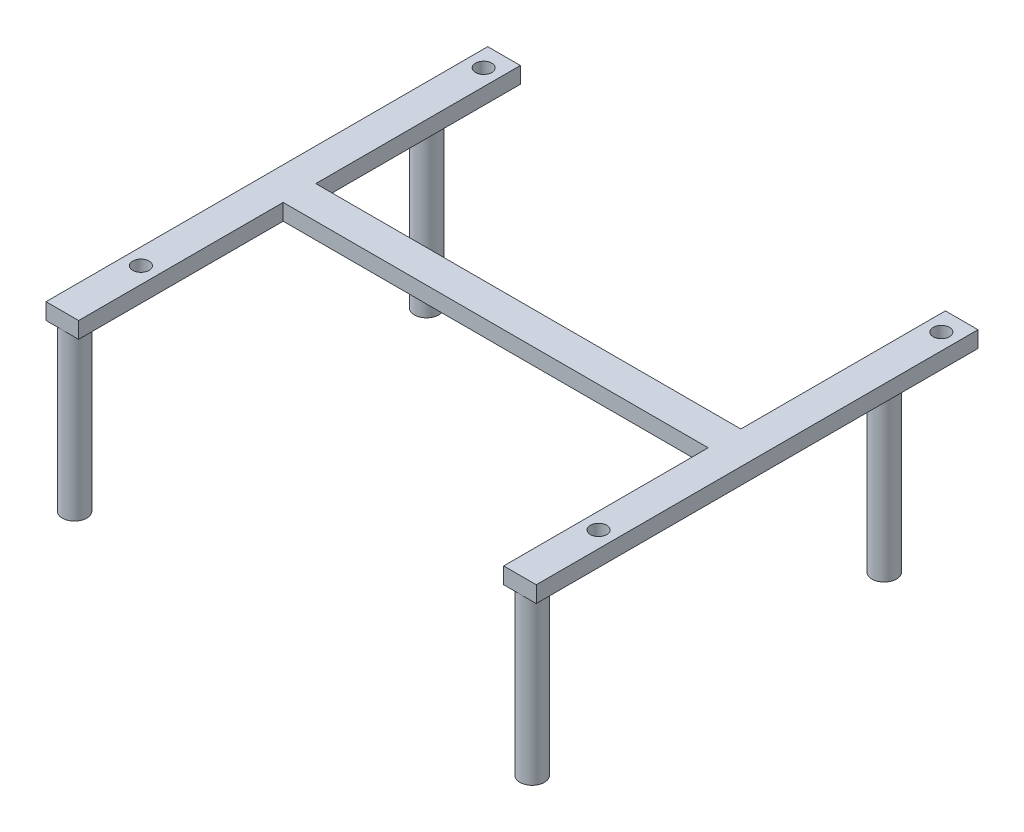
SolidWorks part; units mm, degrees
ref_plane "前视基准面" through (0, 0, 0) normal (0, 0, 1) x (1, 0, 0)
ref_plane "上视基准面" through (0, 0, 0) normal (0, 1, 0) x (1, 0, 0)
ref_plane "右视基准面" through (0, 0, 0) normal (1, 0, 0) x (0, 0, -1)
other "Configuration Table"
sketch "草图1" plane through (0, 0, 0) normal (0, 1, 0) x (1, 0, 0)
  line L0 (0, 43.18) -> (0, 0) construction
  line L1 (56.13, 43.18) -> (0, 43.18) construction
  line L2 (56.13, 0) -> (56.13, 43.18) construction
  line L3 (28.065, 43.18) -> (28.065, 39.1656) construction
  line L4 (56.13, 43.18) -> (0, 43.18) construction
  circle A0 centre (0, 0) radius 1.5
  circle A1 centre (0, 43.18) radius 1.5
  circle A2 centre (56.13, 43.18) radius 1.5
  circle A3 centre (56.13, 0) radius 1.5
  point P10 (28.065, 43.18)
  dimension "D1" = 3
  dimension "D2" = 3
  dimension "D4" = 3
  dimension "D6" = 3
  dimension "D3" = 43.18
  dimension "D5" = 56.13
  dimension "D7" = 43.18
extrude "凸台-拉伸1" add sketch "草图1" along normal blind 20
sketch "草图2" plane through (0, 20, 0) normal (0, 1, 0) x (1, 0, 0)
  line L0 (-2, 52.68) -> (-2, -1.5)
  line L1 (-2, -1.5) -> (2, -1.5)
  line L3 (2, 52.68) -> (-2, 52.68)
  line L5 (54.13, -1.5) -> (58.13, -1.5)
  line L6 (58.13, -1.5) -> (58.13, 52.68)
  line L7 (58.13, 52.68) -> (54.13, 52.68)
  line L8 (2, 27.59) -> (54.13, 27.59)
  line L10 (54.13, 23.59) -> (2, 23.59)
  line L13 (54.13, 52.68) -> (54.13, 27.59)
  line L14 (2, 52.68) -> (2, 27.59)
  line L15 (2, 23.59) -> (2, -1.5)
  line L16 (54.13, 23.59) -> (54.13, -1.5)
  circle A0 centre (0, 43.18) radius 1.5 construction
  circle A1 centre (0, 0) radius 1.5 construction
  circle A2 centre (56.13, 43.18) radius 1.5 construction
  circle A4 centre (56.13, 0) radius 1.5 construction
  point P22 (-2, 25.59)
  dimension "D8" = 2
  dimension "D1" = 9.5
  dimension "D2" = 9.5
  dimension "D3" = 4
  dimension "D4" = 2
  dimension "D5" = 4
  dimension "D6" = 2
  dimension "D7" = 4
extrude "凸台-拉伸2" add sketch "草图2" along normal blind 2
sketch "草图4" plane through (0, 22, 0) normal (0, 1, 0) x (1, 0, 0)
  line L1 (28.065, 27.59) -> (28.065, 23.59) construction
  line L2 (0, -1.5) -> (0, 52.68) construction
  line L3 (-2, -1.5) -> (2, -1.5) construction
  line L4 (2, 52.68) -> (-2, 52.68) construction
  line L7 (54.13, 27.59) -> (2, 27.59) construction
  circle A0 centre (0, 50.18) radius 1
  circle A1 centre (0, 8.143) radius 1
  circle A2 centre (56.13, 8.143) radius 1
  circle A3 centre (56.13, 50.18) radius 1
  point P16 (28.065, 27.59)
  dimension "D2" = 2
  dimension "D3" = 2
  dimension "D1" = 42.037
  dimension "D4" = 2.5
extrude "切除-拉伸1" cut sketch "草图4" against normal up to next (2 mm away)
